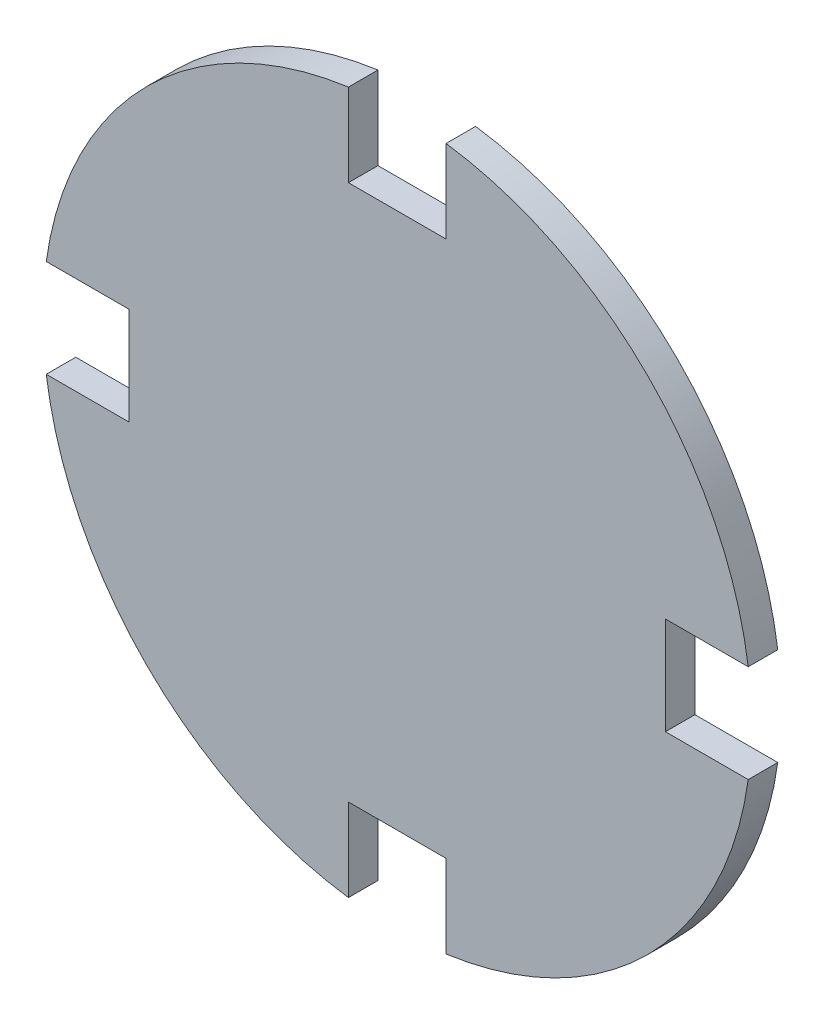
SolidWorks part; units mm, degrees
material "Custom Plastic"
ref_plane "Front Plane" through (0, 0, 0) normal (0, 0, 1) x (1, 0, 0)
ref_plane "Top Plane" through (0, 0, 0) normal (0, 1, 0) x (1, 0, 0)
ref_plane "Right Plane" through (0, 0, 0) normal (1, 0, 0) x (0, 0, -1)
sketch "Sketch1" plane through (0, 0, 0) normal (0, 0, 1) x (1, 0, 0)
  line L0 (150.9462, -21) -> (115.332, -21)
  line L1 (163.332, -21) -> (115.332, -21) construction
  line L2 (115.332, -21) -> (115.332, 21)
  line L3 (115.332, 21) -> (150.9462, 21)
  line L4 (115.332, 21) -> (163.332, 21) construction
  line L5 (-21, -163.332) -> (-21, -115.332) construction
  line L7 (-21, -150.9462) -> (-21, -115.332)
  line L8 (-21, -115.332) -> (21, -115.332)
  line L9 (21, -150.9462) -> (21, -115.332)
  line L10 (-21, 115.332) -> (-21, 163.332) construction
  line L11 (-150.9462, 21) -> (-115.332, 21)
  line L13 (-150.9462, -21) -> (-115.332, -21)
  line L14 (-115.332, 21) -> (-115.332, -21)
  line L16 (-21, 150.9462) -> (-21, 115.332)
  line L17 (-21, 115.332) -> (21, 115.332)
  line L18 (21, 150.9462) -> (21, 115.332)
  arc A0 (150.9462, 21) -> (21, 150.9462) centre (0, 0) ccw
  arc A2 (21, -150.9462) -> (150.9462, -21) centre (0, 0) ccw
  arc A3 (-150.9462, -21) -> (-21, -150.9462) centre (0, 0) ccw
  arc A4 (-21, 150.9462) -> (-150.9462, 21) centre (0, 0) ccw
  dimension "D1" = 304.8
  dimension "D2" = 35.6142
extrude "Boss-Extrude1" add sketch "Sketch1" along normal mid plane 12.7 contours A3 L7 L8 L9 A2 L0 L2 L3 A0 L18 L17 L16 A4 L11 L14 L13
